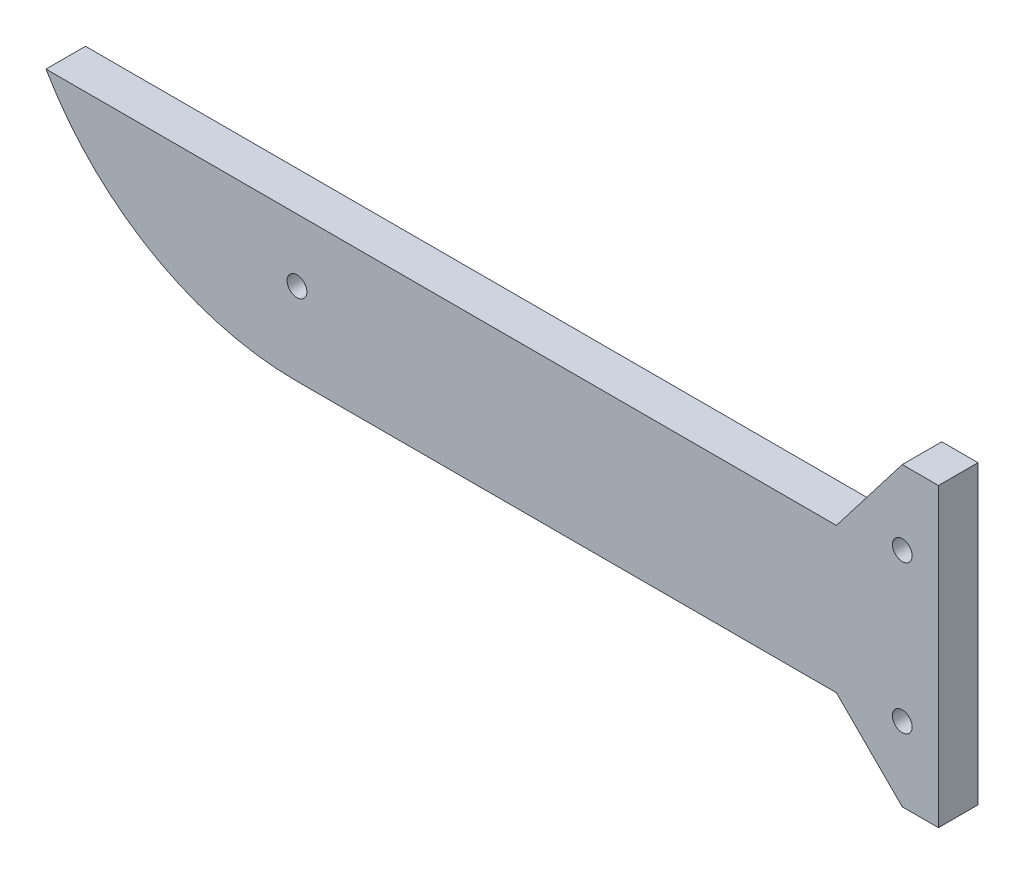
SolidWorks part; units mm, degrees
ref_plane "Front Plane" through (0, 0, 0) normal (0, 0, 1) x (1, 0, 0)
ref_plane "Top Plane" through (0, 0, 0) normal (0, 1, 0) x (1, 0, 0)
ref_plane "Right Plane" through (0, 0, 0) normal (1, 0, 0) x (0, 0, -1)
sketch "Sketch1" plane through (0, 0, 0) normal (0, 0, 1) x (1, 0, 0)
  line L0 (0, -3) -> (120, -3)
  line L1 (120, -25) -> (38.1051, -25)
  line L2 (120, -3) -> (130, 10)
  line L3 (130, 10) -> (135.5, 10)
  line L4 (135.5, 10) -> (135.5, -35)
  line L5 (135.5, -35) -> (130, -35)
  line L6 (130, -35) -> (120, -25)
  line L7 (120, -3) -> (120, -25) construction
  line L8 (130, 10) -> (130, -35) construction
  line L9 (10, 0) -> (120, 0) construction
  line L10 (120, 0) -> (120, -3) construction
  line L11 (0, 0) -> (0, -3) construction
  line L12 (0, 0) -> (0, 5) construction
  line L13 (0, 5) -> (5, 5) construction
  line L14 (120, 0) -> (130, 10) construction
  line L15 (135.5, 10) -> (151.5, 10) construction
  line L16 (151.5, 10) -> (151.5, -7.5) construction
  line L17 (151.5, -7.5) -> (145.5, -7.5) construction
  line L18 (145.5, -7.5) -> (145.5, -1.5) construction
  line L19 (145.5, -1.5) -> (138.5, -1.5) construction
  line L20 (138.5, -1.5) -> (138.5, -17.5) construction
  line L21 (138.5, -17.5) -> (151.5, -17.5) construction
  line L22 (151.5, -17.5) -> (151.5, -35) construction
  line L23 (151.5, -35) -> (145.5, -35) construction
  line L24 (145.5, -35) -> (145.5, -29) construction
  line L25 (145.5, -29) -> (138.5, -29) construction
  line L26 (138.5, -29) -> (138.5, -35) construction
  line L27 (138.5, -35) -> (135.5, -35) construction
  line L28 (38.1051, -25) -> (38.1051, 0) construction
  arc A0 (0, -3) -> (38.1051, -25) centre (38.1051, 19) ccw
  arc A1 (5, 5) -> (10, 0) centre (10, 5) ccw construction
  circle A2 centre (130, -1.25) radius 1.5
  circle A3 centre (130, -23.75) radius 1.5
  circle A4 centre (38.1051, -12.5) radius 1.5
  dimension "D13" = 3
  dimension "D1" = 22
  dimension "D2" = 44
  dimension "D6" = 5.5
  dimension "D3" = 45
  dimension "D4" = 45
  dimension "D5" = 3
  dimension "D7" = 45
  dimension "D8" = 5
  dimension "D9" = 5
  dimension "D10" = 110
  dimension "D11" = 11.25
  dimension "D12" = 11.25
  dimension "D14" = 17.5
  dimension "D15" = 6
  dimension "D16" = 6
  dimension "D17" = 7
  dimension "D18" = 3
extrude "Boss-Extrude1" add sketch "Sketch1" along normal blind 6
equation "\"D11@Sketch1\"=\"D3@Sketch1\"/4"
equation "\"D12@Sketch1\"=\"D11@Sketch1\""
equation "\"M3_d\"= \"M3_d@filament_spool_holder.Assembly\""
equation "\"D13@Sketch1\"=\"M3_d\""
equation "\"spool_holder_l\"= \"spool_holder_l@filament_spool_holder.Assembly\""
equation "\"D10@Sketch1\"=\"spool_holder_l\""
equation "\"housing_t\"= \"housing_t@filament_spool_holder.Assembly\""
equation "\"D1@Boss-Extrude1\"=\"housing_t\""
equation "\"D17@Sketch1\"=\"housing_t\" + 1"
equation "\"D15@Sketch1\"=\"housing_t\""
